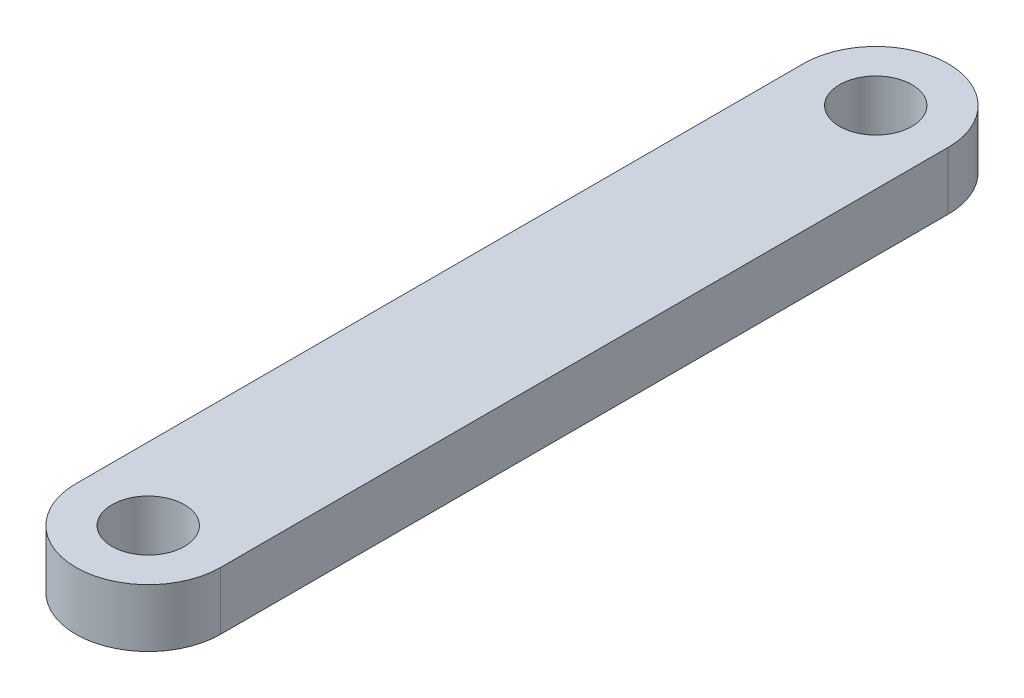
SolidWorks part; units mm, degrees
ref_plane "Front Plane" through (0, 0, 0) normal (0, 0, 1) x (1, 0, 0)
ref_plane "Top Plane" through (0, 0, 0) normal (0, 1, 0) x (1, 0, 0)
ref_plane "Right Plane" through (0, 0, 0) normal (1, 0, 0) x (0, 0, -1)
sketch "Sketch1" plane through (0, 0, 0) normal (0, 1, 0) x (1, 0, 0)
  line L0 (-2.5, 0) -> (-2.5, 25.11)
  line L1 (2.5, 25.11) -> (2.5, 0)
  circle A0 centre (0, 25.11) radius 1
  circle A1 centre (0, 0) radius 1
  arc A2 (-2.5, 0) -> (2.5, 0) centre (0, 0) ccw
  arc A3 (2.5, 25.11) -> (-2.5, 25.11) centre (0, 25.11) ccw
  dimension "D2" = 2
  dimension "D3" = 5
  dimension "D4" = 2
  dimension "D5" = 25.11
extrude "Boss-Extrude1" add sketch "Sketch1" along normal blind 2
other "Move Face1" face at (0, 2, -24.11) face at (0, 2, 1) parameters "D1"=0.25
